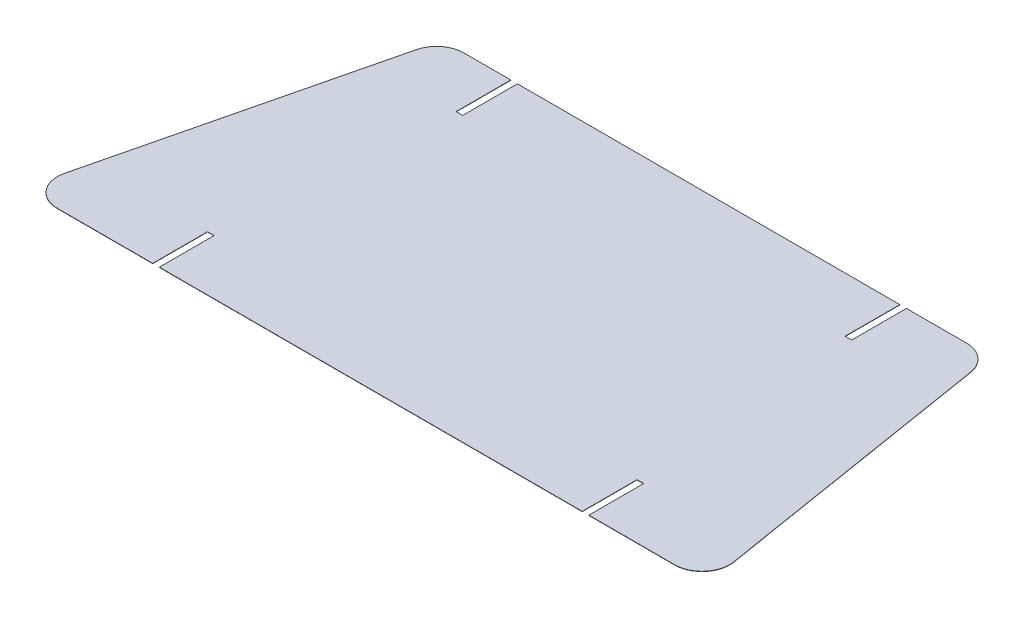
SolidWorks part; units mm, degrees
ref_plane "Front Plane" through (0, 0, 0) normal (0, 0, 1) x (1, 0, 0)
ref_plane "Top Plane" through (0, 0, 0) normal (0, 1, 0) x (1, 0, 0)
ref_plane "Right Plane" through (0, 0, 0) normal (1, 0, 0) x (0, 0, -1)
sketch "Parametric Corte Laser" plane through (0, 0, 0) normal (0, 1, 0) x (1, 0, 0)
  line L0 (0.4466, -11.9204) -> (0.4466, 12.5745) construction
  line L1 (-22.4557, -12.3319) -> (-15.482, -12.3319)
  line L2 (-24.3992, -9.8597) -> (-19.3741, 10.8178)
  line L3 (-17.4307, 12.3455) -> (-14.0029, 12.3455)
  line L4 (24.6236, -10.0117) -> (21.2696, 10.6657)
  line L5 (-25, -12.3319) -> (-15.482, -12.3319) construction
  line L6 (16.3752, -8.3319) -> (16.3752, -12.3319)
  line L7 (-14.0029, 12.3455) -> (-14.0029, 8.3455)
  line L8 (0.4466, 0.327) -> (22.9466, 0.327) construction
  line L9 (-15, -12.3319) -> (-15, -8.3319)
  line L10 (-13.5209, 12.3455) -> (-13.5209, 8.3455)
  line L11 (-15, -8.3319) -> (-15, -12.3319)
  line L12 (-14.0029, 8.3455) -> (-13.5209, 8.3455)
  line L13 (15.8932, -8.3319) -> (16.3752, -8.3319)
  line L14 (-13.5209, 12.3455) -> (19.2954, 12.3455)
  line L15 (-15, -8.3319) -> (-15.482, -8.3319)
  line L16 (14.8961, 8.3455) -> (14.4141, 8.3455)
  line L17 (-15.482, -8.3319) -> (-15.482, -12.3319)
  line L18 (-15, -12.3319) -> (22.6494, -12.3319)
  line L19 (15.8932, -8.3319) -> (15.8932, -12.3319)
  line L20 (14.4141, 12.3455) -> (14.4141, 8.3455)
  line L21 (15.8932, -12.3319) -> (15.8932, -8.3319)
  line L22 (14.8961, 12.3455) -> (14.8961, 8.3455)
  arc A0 (24.6236, -10.0117) -> (22.6494, -12.3319) centre (22.6494, -10.3319) cw
  arc A1 (-22.4557, -12.3319) -> (-24.3992, -9.8597) centre (-22.4557, -10.3319) cw
  arc A2 (21.2696, 10.6657) -> (19.2954, 12.3455) centre (19.2954, 10.3455) ccw
  arc A3 (-19.3741, 10.8178) -> (-17.4307, 12.3455) centre (-17.4307, 10.3455) cw
  point P26 (25, -12.3319)
  point P32 (20.9971, 12.3455)
  point P35 (-19.0029, 12.3455)
  dimension "D8" = 2
  dimension "D1" = 50
  dimension "D2" = 25
  dimension "D3" = 40
  dimension "D6" = 4
  dimension "D4" = 10
  dimension "D5" = 0.482
  dimension "D7" = 5
extrude "Boss-Extrude1" add sketch "Parametric Corte Laser" along normal blind 0.02 contours A3 L2 A1 L1 L17 L15 L9 L18 L19 L13 L6 A0 L4 A2 L14 L22 L16 L20 L10 L12 L7 L3
equation "\"ap\"= 50'ancho pieza"
equation "\"D2@Parametric Corte Laser\" = \"ap\" *  ( .5 ) "
equation "\"D3@Parametric Corte Laser\" = \"ap\" * .8"
equation "\"t\"= .5mm'thickness material"
equation "\"D6@Parametric Corte Laser\" = \"ap\" *  ( .08 ) "
equation "\"D5@Parametric Corte Laser\"=\"t\"-.018"
equation "\"D7@Parametric Corte Laser\"=(\"ap\"*(.1))"
